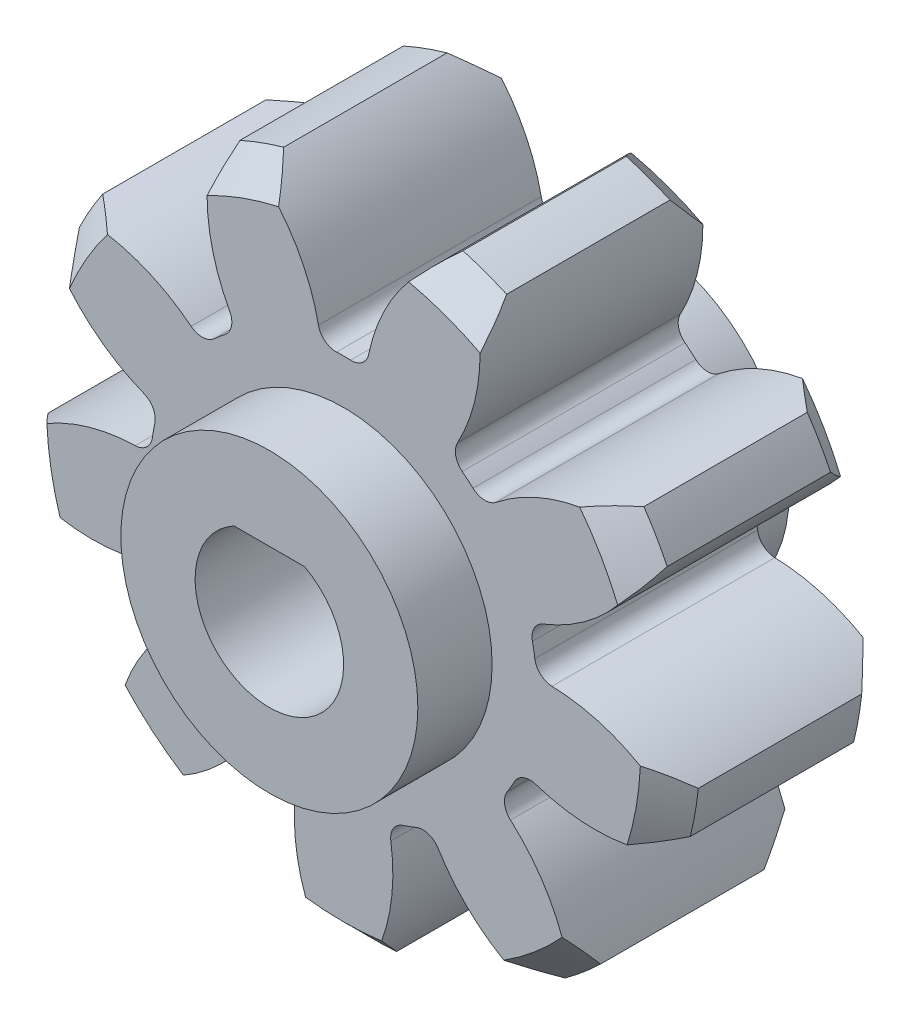
SolidWorks part; units mm, degrees
ref_plane "Přední rovina" through (0, 0, 0) normal (0, 0, 1) x (1, 0, 0)
ref_plane "Horní rovina" through (0, 0, 0) normal (0, 1, 0) x (1, 0, 0)
ref_plane "Pravá rovina" through (0, 0, 0) normal (1, 0, 0) x (0, 0, -1)
sketch "Skica1" plane through (0, 0, 0) normal (0, 0, 1) x (1, 0, 0)
  circle A0 centre (0, 0) radius 11
  circle A1 centre (0, 0) radius 9 construction
  dimension "D1" = 22
  dimension "D2" = 18
extrude "Přidat vysunutím1" add sketch "Skica1" along normal blind 7.5
sketch "Skica2" plane through (0, 0, 0) normal (0, 0, 1) x (1, 0, 0)
  line L0 (0, 11) -> (0, 0) construction
  line L1 (0, 0) -> (7.0707, 8.4265) construction
  line L2 (3.7622, 10.3366) -> (0, 0) construction
  line L3 (-0.7631, 6.4551) -> (0, 0) construction
  line L4 (-1.5628, 8.8633) -> (1.5628, 8.8633) construction
  line L5 (1.5628, 8.8633) -> (4.5, 7.7942) construction
  line L6 (-2.6145, 10.6848) -> (0, 6.1564) construction
  circle A0 centre (0, 0) radius 7 construction
  circle A2 centre (0, 0) radius 11 construction
  arc A3 (-3.0166, 10.5783) -> (-0.7631, 6.4551) centre (-7.0139, 5.7161) cw
  arc A4 (3.0166, 10.5783) -> (0.7631, 6.4551) centre (7.0139, 5.7161) ccw
  circle A5 centre (0, 0) radius 9 construction
  arc A6 (-3.0166, 10.5783) -> (3.0166, 10.5783) centre (0, 0) cw
  arc A7 (0.7631, 6.4551) -> (-0.7631, 6.4551) centre (0, 0) ccw
  dimension "D3" = 40
  dimension "D4" = 30
  dimension "D1" = 0.5
extrude "Odebrat vysunutím1" cut sketch "Skica2" along normal blind 7.5
fillet "Zaoblit1" radius 0.6 2 edges at (0.7631, 6.4551, 3.75) (-0.7631, 6.4551, 3.75)
chamfer "Zkosení1" distance 1 2 edges at (0, -11, 0) (0, -11, 7.5)
pattern_circular "Kruhové pole1" count 9 every 40 about axis through (0, 0, 0) along (0, 0, 1) of "Odebrat vysunutím1", "Zaoblit1"
sketch "Skica3" plane through (0, 0, 0) normal (0, 0, 1) x (1, 0, 0)
  circle A0 centre (0, 0) radius 5
  dimension "D1" = 10
extrude "Přidat vysunutím2" add sketch "Skica3" against normal blind 2.5 and the other way blind 10
sketch "Skica5" plane through (0, 0, 10) normal (0, 0, 1) x (1, 0, 0)
  line L0 (-1.1874, 2.2) -> (1.1874, 2.2)
  line L1 (0, -3.3491) -> (0, 4.293) construction
  arc A0 (-1.1874, 2.2) -> (1.1874, 2.2) centre (0, 0) ccw
  dimension "D1" = 5
  dimension "D2" = 2.2
  dimension "D3" = 2.3749
extrude "Odebrat vysunutím2" cut sketch "Skica5" against normal blind 20
equation "\"Module\"= 2mm"
equation "\"Number of teeth\" = 9"
equation "\"Pressure angle\"= 30"
equation "\"D1@Skica1\"= (\"Number of teeth\" + 2) * \"Module\""
equation "\"D2@Skica1\"= \"Number of teeth\" * \"Module\""
equation "\"D2@Skica2\"= \"Module\" * 2"
equation "\"D3@Skica2\"= 360 / \"Number of teeth\""
equation "\"D4@Skica2\"= \"Pressure angle\""
equation "\"D1@Zaoblit1\"= 0.3 * \"Module\""
equation "\"D1@Kruhové pole1\"= \"Number of teeth\""
equation "\"D2@Kruhové pole1\"= 360 / \"Number of teeth\""
